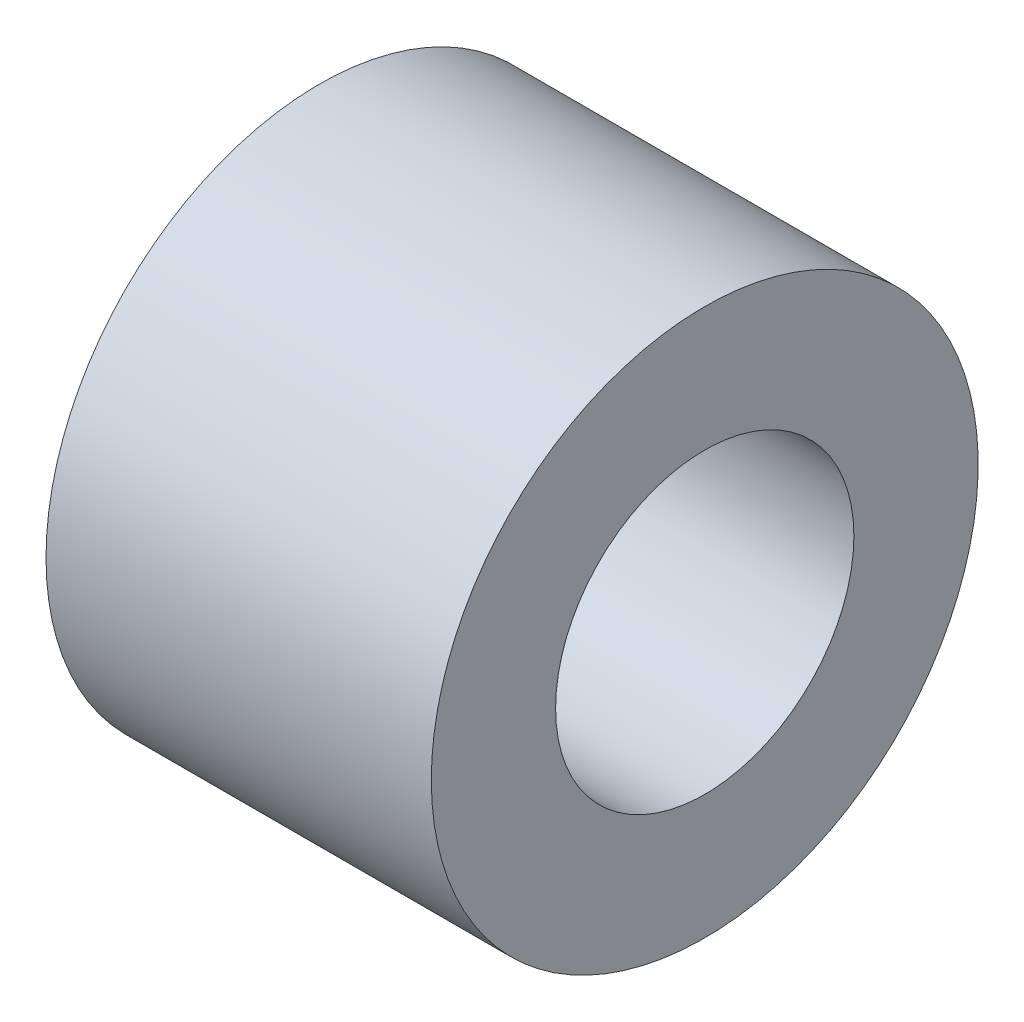
SolidWorks part; units mm, degrees
material "Д16 ГОСТ 4784-97"
ref_plane "Front Plane" through (0, 0, 0) normal (0, 0, 1) x (1, 0, 0)
ref_plane "Top Plane" through (0, 0, 0) normal (0, 1, 0) x (1, 0, 0)
ref_plane "Right Plane" through (0, 0, 0) normal (1, 0, 0) x (0, 0, -1)
sketch "Skizze2" plane through (0, 0, 0) normal (0, 1, 0) x (1, 0, 0)
  line L0 (0, 0) -> (0, 6)
  line L1 (0, 0) -> (0, -6)
  line L2 (0, -6) -> (15.5, -6)
  line L3 (15.5, -6) -> (15.5, 6)
  line L4 (15.5, 6) -> (0, 6)
  line L5 (0, 0) -> (0, 11)
  line L6 (0, 0) -> (0, -11)
  line L7 (0, -11) -> (15.5, -11)
  line L8 (15.5, -11) -> (15.5, 0)
  line L9 (15.5, 0) -> (15.5, 11)
  line L10 (15.5, 11) -> (0, 11)
  line L11 (0, 0) -> (15.5, 0)
revolve "Rotation1" add sketch "Skizze2" angle 360 about L11
